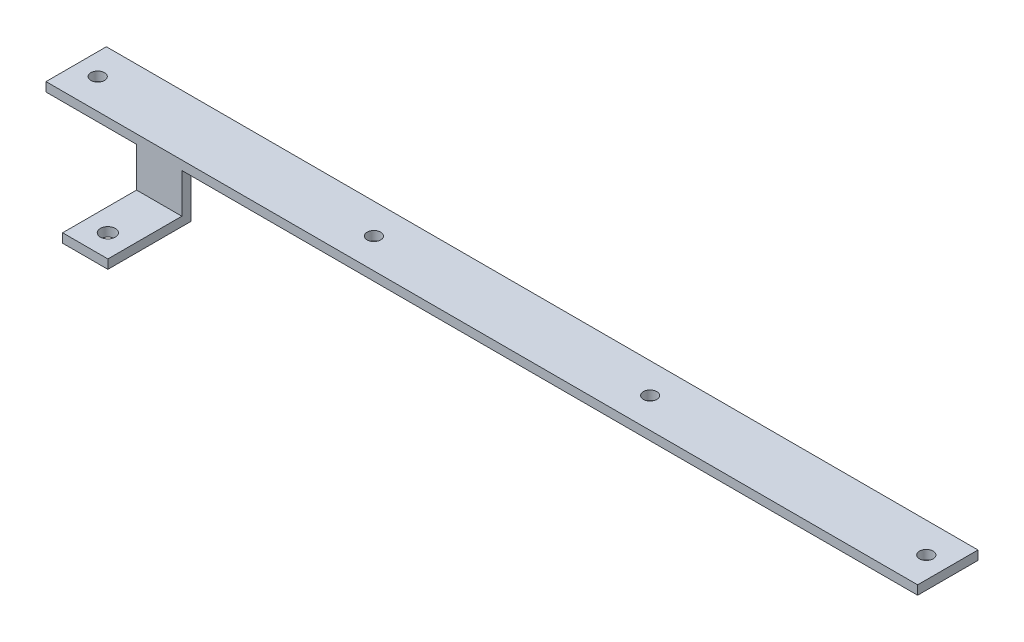
SolidWorks part; units mm, degrees
material "ASTM A36 Steel"
ref_plane "Front Plane" through (0, 0, 0) normal (0, 0, 1) x (1, 0, 0)
ref_plane "Top Plane" through (0, 0, 0) normal (0, 1, 0) x (1, 0, 0)
ref_plane "Right Plane" through (0, 0, 0) normal (1, 0, 0) x (0, 0, -1)
sketch "Sketch1" plane through (0, 0, 0) normal (0, 1, 0) x (1, 0, 0)
  line L1 (-577.5, -40) -> (577.5, -40)
  line L2 (-577.5, -40) -> (-577.5, 40)
  line L3 (-577.5, 40) -> (577.5, 40)
  line L4 (577.5, -40) -> (577.5, 40)
  line L5 (-577.5, -40) -> (577.5, 40) construction
  line L6 (-577.5, 40) -> (577.5, -40) construction
  point P0 (0, 0)
  dimension "D1" = 80
  dimension "D2" = 1155
extrude "Boss-Extrude1" add sketch "Sketch1" along normal blind 12
sketch "Sketch2" plane through (0, 12, 0) normal (0, 1, 0) x (1, 0, 0)
  line L0 (-577.5, 40) -> (-577.5, -40) construction
  circle A0 centre (-549, 0) radius 9
  dimension "D1" = 18
  dimension "D2" = 28.5
extrude "Cut-Extrude1" cut sketch "Sketch2" against normal through all both and the other way through all
pattern_linear "LPattern1" count 4 spacing 366 along (1, 0, 0) of "Cut-Extrude1"
sketch "Sketch3" plane through (0, 12, 0) normal (0, 1, 0) x (1, 0, 0)
  line L0 (-577.5, -40) -> (577.5, -40) construction
  line L1 (-457.5, -40) -> (-397.5, -40)
  line L2 (-457.5, -40) -> (-457.5, -138)
  line L3 (-457.5, -138) -> (-397.5, -138)
  line L4 (-397.5, -40) -> (-397.5, -138)
  line L5 (-577.5, 40) -> (-577.5, -40) construction
  circle A0 centre (-427.5, -108) radius 10
  dimension "D3" = 20
  dimension "D4" = 30
  dimension "D1" = 60
  dimension "D2" = 98
  dimension "D5" = 120
extrude "Boss-Extrude2" add sketch "Sketch3" against normal blind 12
sketch "Sketch4" plane through (0, 0, 0) normal (0, -1, 0) x (-1, 0, 0)
  line L1 (457.5, -40) -> (397.5, -40)
  line L2 (457.5, -40) -> (457.5, -28)
  line L3 (457.5, -28) -> (397.5, -28)
  line L4 (397.5, -40) -> (397.5, -28)
  dimension "D1" = 12
extrude "Boss-Extrude3" add sketch "Sketch4" along normal blind 52.5
sketch "Sketch6" plane through (0, -52.5, 0) normal (0, -1, 0) x (1, 0, 0)
  line L1 (-457.5, 28) -> (-397.5, 28)
  line L2 (-457.5, 28) -> (-457.5, 138)
  line L3 (-457.5, 138) -> (-397.5, 138)
  line L4 (-397.5, 28) -> (-397.5, 138)
  circle A0 centre (-427.5, 108) radius 10
extrude "Boss-Extrude4" add sketch "Sketch6" along normal blind 12 contours L2 L3 L4 L1 | A0
sketch "Sketch7" plane through (0, 12, 0) normal (0, 1, 0) x (1, 0, 0)
  line L1 (-457.5, -138) -> (-397.5, -138)
  line L2 (-457.5, -138) -> (-457.5, -40)
  line L3 (-457.5, -40) -> (-397.5, -40)
  line L4 (-397.5, -138) -> (-397.5, -40)
extrude "Cut-Extrude2" cut sketch "Sketch7" against normal blind 12
